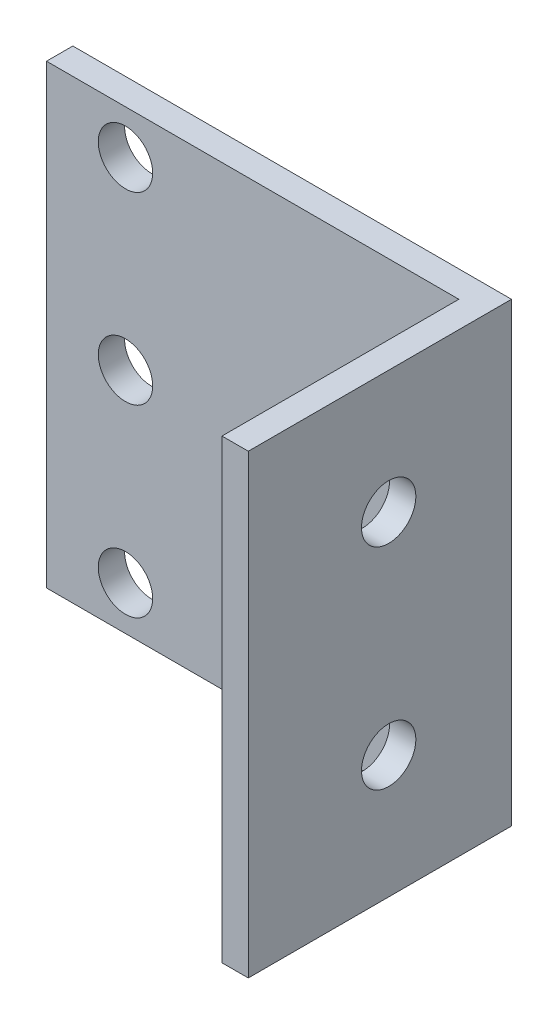
SolidWorks part; units mm, degrees
ref_plane "Front Plane" through (0, 0, 0) normal (0, 0, 1) x (1, 0, 0)
ref_plane "Top Plane" through (0, 0, 0) normal (0, 1, 0) x (1, 0, 0)
ref_plane "Right Plane" through (0, 0, 0) normal (1, 0, 0) x (0, 0, -1)
sketch "Sketch1" plane through (0, 0, 0) normal (0, 0, 1) x (1, 0, 0)
  line L0 (0, 10.5) -> (0, -10.5) construction
  line L1 (0, 0) -> (20.5, 0) construction
  line L3 (5, 13) -> (5, -13) construction
  line L5 (-4.5, 13) -> (20.5, 13)
  line L6 (-4.5, 13) -> (-4.5, -13)
  line L7 (-4.5, -13) -> (20.5, -13)
  line L8 (20.5, 13) -> (20.5, -13)
  circle A0 centre (0, 10.5) radius 1.55
  circle A1 centre (0, 0) radius 1.55
  circle A2 centre (0, -10.5) radius 1.55
  dimension "D1" = 3.1
  dimension "D2" = 5
  dimension "D3" = 25
  dimension "D4" = 26
  dimension "D5" = 4.5
  dimension "D6" = 10.5
extrude "Boss-Extrude1" add sketch "Sketch1" along normal blind 1.5
sketch "Sketch2" plane through (0, 0, 1.5) normal (0, 0, 1) x (1, 0, 0)
  line L0 (-4.5, -13) -> (20.5, -13) construction
  line L1 (20.5, 13) -> (19, 13)
  line L2 (20.5, 13) -> (20.5, -13)
  line L3 (20.5, -13) -> (19, -13)
  line L4 (19, 13) -> (19, -13)
  dimension "D1" = 1.5
extrude "Boss-Extrude2" add sketch "Sketch2" along normal blind 13.5
sketch "Sketch3" plane through (20.5, 0, 0) normal (1, 0, 0) x (0, 0, -1)
  line L0 (-7, 13) -> (-7, -13) construction
  line L1 (-15, 13) -> (0, 13) construction
  line L2 (-15, -13) -> (0, -13) construction
  line L3 (-15, -13) -> (-15, 13) construction
  circle A0 centre (-7, 6) radius 1.55
  circle A2 centre (-7, -6) radius 1.55
  dimension "D2" = 3.1
  dimension "D1" = 8
  dimension "D3" = 7
  dimension "D4" = 7
extrude "Cut-Extrude1" cut sketch "Sketch3" against normal blind 13
